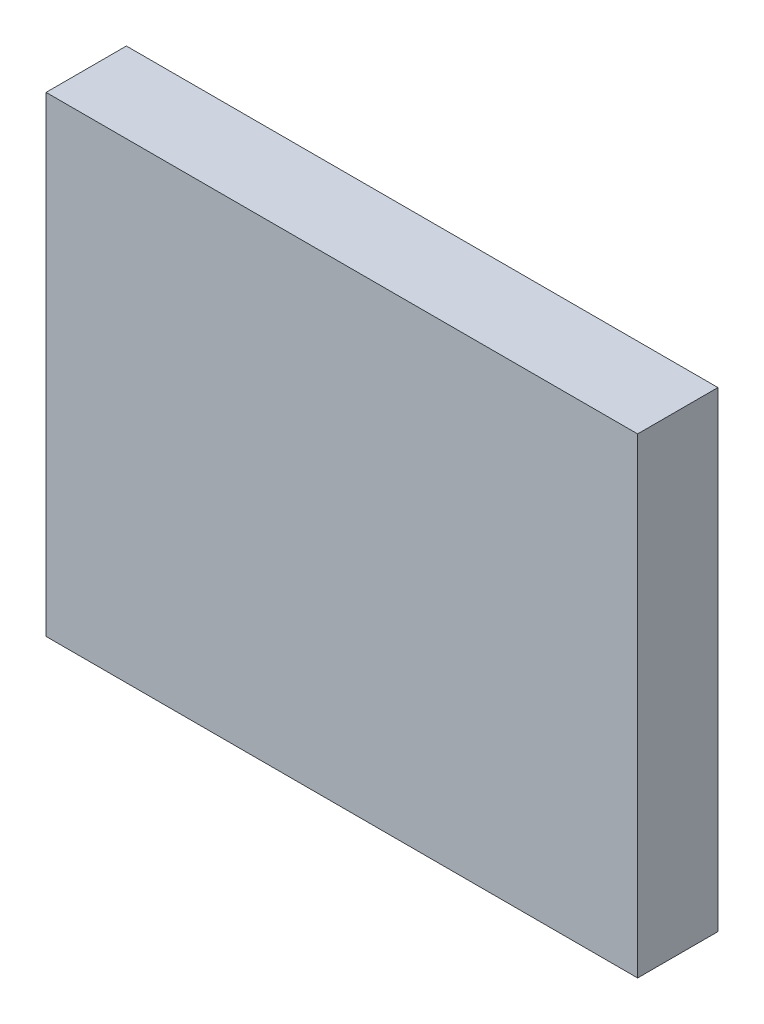
SolidWorks part; units mm, degrees
ref_plane "Front Plane" through (0, 0, 0) normal (0, 0, 1) x (1, 0, 0)
ref_plane "Top Plane" through (0, 0, 0) normal (0, 1, 0) x (1, 0, 0)
ref_plane "Right Plane" through (0, 0, 0) normal (1, 0, 0) x (0, 0, -1)
sketch "Sketch1" plane through (0, 0, 0) normal (0, 0, 1) x (1, 0, 0)
  line L0 (0, 0) -> (73.66, 0)
  line L1 (0, 0) -> (0, 58.674)
  line L2 (0, 58.674) -> (73.66, 58.674)
  line L3 (73.66, 58.674) -> (73.66, 0)
  dimension "D1" = 73.66
  dimension "D2" = 58.674
extrude "Boss-Extrude1" add sketch "Sketch1" along normal blind 10
